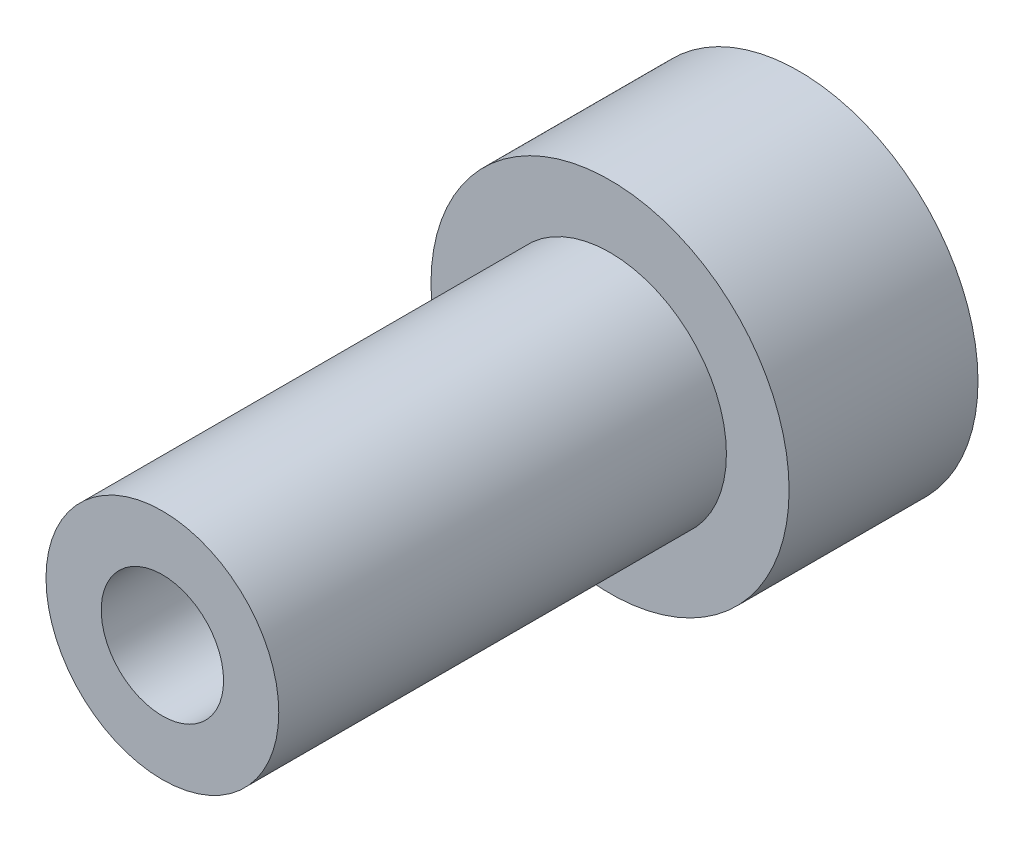
SolidWorks part; units mm, degrees
ref_plane "Front Plane" through (0, 0, 0) normal (0, 0, 1) x (1, 0, 0)
ref_plane "Top Plane" through (0, 0, 0) normal (0, 1, 0) x (1, 0, 0)
ref_plane "Right Plane" through (0, 0, 0) normal (1, 0, 0) x (0, 0, -1)
sketch "Sketch1" plane through (0, 0, 0) normal (0, 0, 1) x (1, 0, 0)
  circle A0 centre (0, 0) radius 6
  circle A1 centre (0, 0) radius 2.05
  dimension "D1" = 12
  dimension "D2" = 4.1
extrude "Boss-Extrude1" add sketch "Sketch1" along normal blind 6.33
sketch "Sketch2" plane through (0, 0, 6.33) normal (0, 0, 1) x (1, 0, 0)
  circle A0 centre (0, 0) radius 2.05
  circle A1 centre (0, 0) radius 3.9
  dimension "D1" = 7.8
extrude "Boss-Extrude2" add sketch "Sketch2" along normal blind 15
